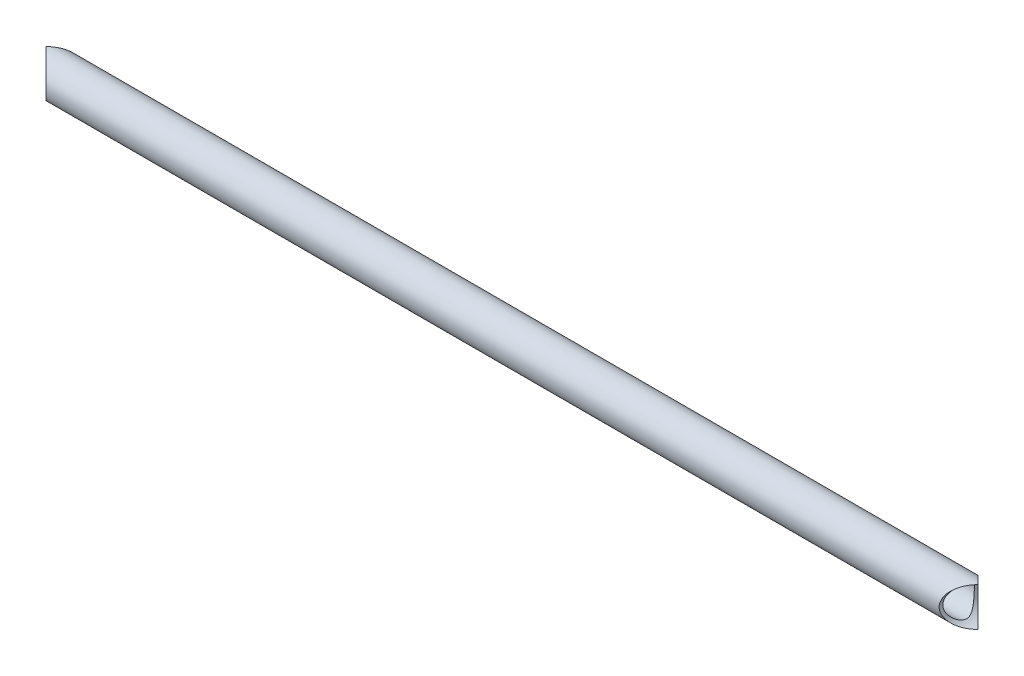
SolidWorks part; units mm, degrees
material "AISI 304"
ref_plane "Plano frontal" through (0, 0, 0) normal (0, 0, 1) x (1, 0, 0)
ref_plane "Plano superior" through (0, 0, 0) normal (0, 1, 0) x (1, 0, 0)
ref_plane "Plano direito" through (0, 0, 0) normal (1, 0, 0) x (0, 0, -1)
ref_plane "Plano1" through (0, 250, 0) normal (0, 1, 0) x (1, 0, 0)
sketch3d "3DSketch1"
  line L0 (803.885, 0, 257.4204) -> (803.885, 0, -257.4204) construction
  line L3 (803.885, 0, -257.4204) -> (0, 0, -200) construction
  line L4 (0, 0, -200) -> (0, 0, 200) construction
  line L5 (0, 0, 200) -> (803.885, 0, 257.4204) construction
sketch "Esboço3" plane through (0, 250, 0) normal (0, 1, 0) x (1, 0, 0)
  line L0 (0, 200) -> (0, -200) construction
  line L1 (0, -200) -> (803.885, -257.4204) construction
  line L2 (803.885, 257.4204) -> (803.885, -257.4204)
  line L3 (803.885, 257.4204) -> (0, 200) construction
sketch "Esboço8" plane through (0, 0, 0) normal (0, 1, 0) x (1, 0, 0)
  line L0 (0, 162.7552) -> (0, -162.7552) construction
  line L1 (0, 0) -> (910, 0) construction
  line L2 (910, 265) -> (910, -265) construction
  line L3 (37.1501, 202.6536) -> (910, 265) construction
  line L4 (37.1501, -202.6536) -> (910, -265) construction
  arc A0 (0, -162.7552) -> (37.1501, -202.6536) centre (40, -162.7552) ccw construction
  arc A1 (0, 162.7552) -> (37.1501, 202.6536) centre (40, 162.7552) cw construction
  point P9 (0, -200)
  point P12 (0, 200)
  dimension "D3" = 40
  dimension "D1" = 400
  dimension "D2" = 910
  dimension "D4" = 530
sketch "Esboço9" plane through (0, 250, 0) normal (0, 1, 0) x (1, 0, 0)
  line L0 (0, 162.7552) -> (0, -162.7552) construction
  line L1 (0, 0) -> (910, 0) construction
  line L2 (910, 265) -> (910, -265) construction
  line L3 (37.1501, 202.6536) -> (910, 265) construction
  line L4 (37.1501, -202.6536) -> (910, -265) construction
  arc A0 (0, -162.7552) -> (37.1501, -202.6536) centre (40, -162.7552) ccw construction
  arc A1 (0, 162.7552) -> (37.1501, 202.6536) centre (40, 162.7552) cw construction
  point P9 (0, -200)
  point P12 (0, 200)
  dimension "D3" = 40
  dimension "D1" = 400
  dimension "D2" = 910
  dimension "D4" = 530
ref_plane "Plano3" through (0, 910, 0) normal (0, 1, 0) x (1, 0, 0)
sketch "Esboço10" plane through (0, 910, 0) normal (0, 1, 0) x (1, 0, 0)
  line L0 (0, 162.4326) -> (0, -163.0779) construction
  line L1 (0, 0) -> (910, 0) construction
  line L2 (910, 265) -> (910, -265) construction
  line L3 (37.1354, 202.3299) -> (910, 265) construction
  line L4 (37.1648, -202.9773) -> (910, -265) construction
  arc A0 (0, -163.0779) -> (37.1648, -202.9773) centre (40, -163.0779) ccw construction
  arc A1 (0, 162.4326) -> (37.1354, 202.3299) centre (40, 162.4326) cw construction
  point P9 (0, -200.3364)
  point P12 (0, 199.6636)
  dimension "D3" = 40
  dimension "D1" = 400
  dimension "D2" = 910
sketch3d "3DSketch3"
  line L0 (910, 0, 265) -> (910, 139.2691, 265)
  line L1 (904.6546, 159.2691, 264.6182) -> (858.6942, 239.0777, 261.3353)
  line L2 (0, 250, 200) -> (803.885, 250, 257.4204) construction
  line L3 (853.5006, 262.564, 260.9643) -> (910, 910, 265)
  line L5 (37.1501, 250, 202.6536) -> (910, 250, 265) construction
  arc A0 (910, 139.2691, 265) -> (904.6546, 159.2691, 264.6182) centre (870.1017, 139.2691, 262.1501) ccw
  arc A1 (858.6942, 239.0777, 261.3353) -> (853.5006, 262.564, 260.9643) centre (893.2472, 259.0777, 263.8034) ccw
  point P10 (910, 149.987, 265)
  point P11 (867.2518, 139.2691, 302.0485)
  point P14 (852.4042, 250, 260.886)
  point P15 (896.097, 259.0777, 223.905)
  point P16 (854.3898, 250, 261.0278)
  dimension "D3" = 40
  dimension "D1" = 150
  dimension "D2" = 145
sketch "Esboço11" plane through (0, 0, 0) normal (0, 1, 0) x (1, 0, 0)
  circle A0 centre (910, -265) radius 7.9375
  dimension "D1" = 15.875
sketch3d "3DSketch4"
  line L0 (910, 0, -265) -> (910, 139.2691, -265)
  line L1 (904.6546, 159.2691, -264.6182) -> (858.6942, 239.0777, -261.3353)
  line L2 (803.885, 250, -257.4204) -> (0, 250, -200) construction
  line L3 (853.5006, 262.564, -260.9643) -> (910, 910, -265)
  line L4 (37.1501, 250, -202.6536) -> (910, 250, -265) construction
  arc A0 (858.6942, 239.0777, -261.3353) -> (853.5006, 262.564, -260.9643) centre (893.2472, 259.0777, -263.8034) ccw
  arc A1 (910, 139.2691, -265) -> (904.6546, 159.2691, -264.6182) centre (870.1017, 139.2691, -262.1501) ccw
  point P10 (852.4042, 250, -260.886)
  point P11 (890.3973, 259.0777, -303.7017)
  point P14 (910, 149.987, -265)
  point P15 (872.9515, 139.2691, -222.2518)
  point P16 (854.3898, 250, -261.0278)
  dimension "D3" = 40
  dimension "D1" = 150
  dimension "D2" = 145
sketch "Esboço12" plane through (0, 0, 0) normal (0, 1, 0) x (1, 0, 0)
  circle A0 centre (910, 265) radius 7.9375
  dimension "D1" = 15.875
sketch "Esboço13" plane through (0, 250, 0) normal (0, 1, 0) x (1, 0, 0)
  line L0 (0, 200) -> (0, -200) construction
  line L1 (0, -200) -> (854.3898, -261.0278) construction
  line L2 (854.3898, -261.0278) -> (854.3898, 261.0278) construction
  line L3 (854.3898, 261.0278) -> (0, 200) construction
  line L4 (854.3898, 261.0278) -> (854.3898, -261.0278)
  line L5 (0, 0) -> (910, 0) construction
  point P6 (854.3898, 150)
  point P7 (854.3898, -150)
  dimension "D1" = 150
  dimension "D2" = 150
sketch3d "3DSketch5"
  line L0 (473.5751, 0, 233.8268) -> (473.5751, 230, 233.8268)
  line L1 (37.1501, 0, 202.6536) -> (910, 0, 265) construction
  line L2 (0, 250, 200) -> (803.885, 250, 257.4204) construction
  line L3 (473.5751, 250, 213.8268) -> (473.5751, 250, -213.8268)
  line L4 (803.885, 250, -257.4204) -> (0, 250, -200) construction
  line L5 (473.5751, 230, -233.8268) -> (473.5751, 0, -233.8268)
  line L6 (803.885, 0, -257.4204) -> (0, 0, -200) construction
  arc A0 (473.5751, 250, -213.8268) -> (473.5751, 230, -233.8268) centre (473.5751, 230, -213.8268) ccw
  arc A1 (473.5751, 230, 233.8268) -> (473.5751, 250, 213.8268) centre (473.5751, 230, 213.8268) ccw
  point P16 (473.5751, 250, -233.8268)
  point P17 (453.5751, 230, -213.8268)
  point P18 (473.5751, 250, 233.8268)
  point P19 (453.5751, 230, 213.8268)
  dimension "D1" = 20
sketch "Esboço15" plane through (0, 250, 0) normal (0, 1, 0) x (1, 0, 0)
  line L0 (854.3898, 150) -> (473.5751, 150)
  line L1 (473.5751, -213.8268) -> (473.5751, 213.8268) construction
  line L2 (0, 0) -> (910, 0) construction
  dimension "D1" = 150
other "Pipe - configured 21.3 X 2.3(5)"
ref_plane "Plano4" through (854.3898, 250, -150) normal (-1, 0, 0) x (0, 0, 1)
sketch "Sketch1" plane through (854.3898, 250, -150) normal (-1, 0, 0) x (0, 0, 1)
  circle A0 centre (0, 0) radius 6.4375
  circle A1 centre (0, 0) radius 7.9375
  point P3 (0, 0)
  dimension "Out_dia" = 15.875
  dimension "D1" = 1.5
sketch "Esboço17" plane through (0, 0, 0) normal (0, 0, 1) x (1, 0, 0)
  circle A0 centre (473.5751, 250) radius 7.9375
  circle A1 centre (854.3898, 250) radius 7.9375
extrude "Corte-extrusão1" cut sketch "Esboço17" against normal through all both and the other way through all
